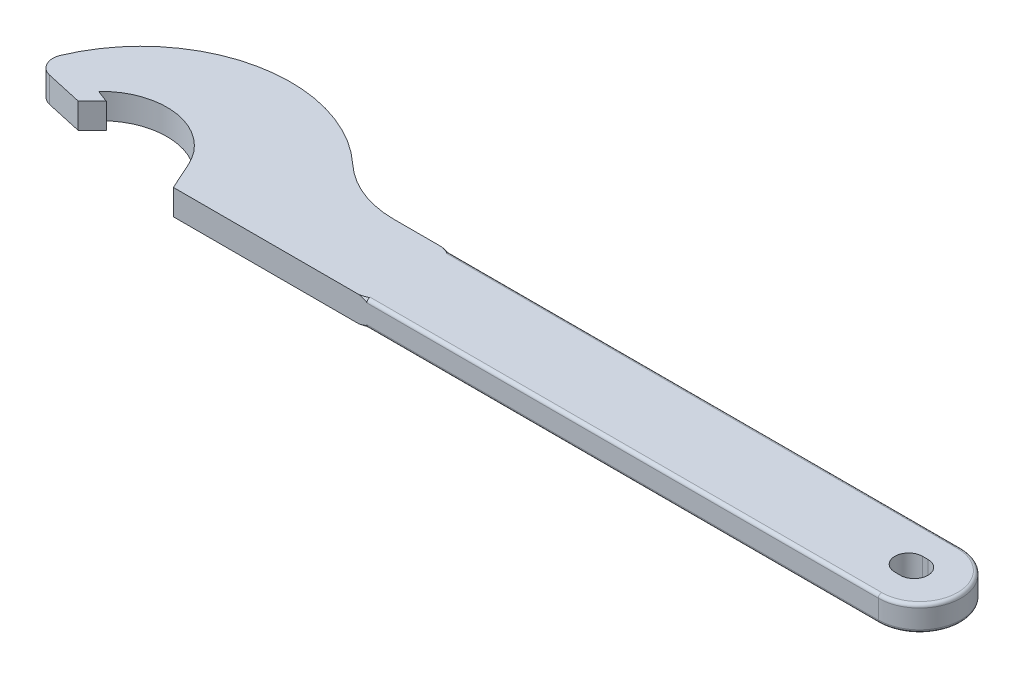
SolidWorks part; units mm, degrees
other "P01 Spanner" parameters "D1"=3.048
ref_plane "Front Plane" through (0, 0, 0) normal (0, 0, 1) x (1, 0, 0)
ref_plane "Top Plane" through (0, 0, 0) normal (0, 1, 0) x (1, 0, 0)
ref_plane "Right Plane" through (0, 0, 0) normal (1, 0, 0) x (0, 0, -1)
sketch "SK_F1_Outline" plane through (0, 0, 0) normal (0, 1, 0) x (1, 0, 0)
  line L0 (-34.3918, 0) -> (50.0534, 0)
  line L1 (50.0534, 9.9007) -> (-17.8812, 9.9007)
  line L2 (-53.4488, 4.2334) -> (-49.0587, 3.2601)
  line L3 (-49.0587, 3.2601) -> (-47.3518, 4.9205)
  line L4 (-47.3518, 4.9205) -> (-48.8359, 5.484)
  line L5 (-35.8603, 3.2601) -> (-34.3918, 0)
  arc A0 (50.0534, 0) -> (50.0534, 9.9007) centre (50.0534, 4.9503) ccw
  arc A1 (-17.8812, 9.9007) -> (-26.016, 13.113) centre (-17.8812, 21.8069) cw
  arc A2 (-26.016, 13.113) -> (-54.8496, 6.9373) centre (-38.2856, 0) ccw
  arc A3 (-54.8496, 6.9373) -> (-53.4488, 4.2334) centre (-53.0193, 6.1707) ccw
  arc A4 (-48.8359, 5.484) -> (-35.8603, 3.2601) centre (-43.0975, 0) cw
extrude "F1_Outline" add sketch "SK_F1_Outline" along normal mid plane 3.048
sketch "SK_F2_Slot" plane through (0, 0, 0) normal (0, 1, 0) x (1, 0, 0)
  line L0 (48.7354, 3.3002) -> (49.3954, 3.3002)
  line L1 (49.3954, 6.6004) -> (48.7354, 6.6004)
  arc A0 (49.3954, 3.3002) -> (49.3954, 6.6004) centre (49.3954, 4.9503) ccw
  arc A1 (48.7354, 6.6004) -> (48.7354, 3.3002) centre (48.7354, 4.9503) ccw
extrude "F2_Slot" cut sketch "SK_F2_Slot" against normal through all and the other way through all
sketch "SK_F3_StraightRounds" plane through (0, 0, 0) normal (1, 0, 0) x (0, 0, -1)
  line L0 (0, 1.1271) -> (-0.254, 1.1271)
  line L1 (-0.254, 1.1271) -> (-0.254, 1.778)
  line L2 (-0.254, 1.778) -> (0.3969, 1.778)
  line L3 (0.3969, 1.778) -> (0.3969, 1.524)
  line L4 (9.9007, 1.1271) -> (10.1547, 1.1271)
  line L5 (10.1547, 1.1271) -> (10.1547, 1.778)
  line L6 (10.1547, 1.778) -> (9.5038, 1.778)
  line L7 (9.5038, 1.778) -> (9.5038, 1.524)
  line L8 (0, -1.1271) -> (-0.254, -1.1271)
  line L9 (-0.254, -1.1271) -> (-0.254, -1.778)
  line L10 (-0.254, -1.778) -> (0.3969, -1.778)
  line L11 (0.3969, -1.778) -> (0.3969, -1.524)
  line L12 (9.9007, -1.1271) -> (10.1547, -1.1271)
  line L13 (10.1547, -1.1271) -> (10.1547, -1.778)
  line L14 (10.1547, -1.778) -> (9.5038, -1.778)
  line L15 (9.5038, -1.778) -> (9.5038, -1.524)
  arc A0 (0.3969, 1.524) -> (0, 1.1271) centre (0.3969, 1.1271) ccw
  arc A1 (9.5038, 1.524) -> (9.9007, 1.1271) centre (9.5038, 1.1271) cw
  arc A2 (0.3969, -1.524) -> (0, -1.1271) centre (0.3969, -1.1271) cw
  arc A3 (9.5038, -1.524) -> (9.9007, -1.1271) centre (9.5038, -1.1271) ccw
extrude "F3a_HandleRounds" cut sketch "SK_F3_StraightRounds" against normal blind 11.2137 and the other way blind 50.0534
ref_plane "PL_EndAxis" through (0, 0, -4.9503) normal (0, 0, 1) x (1, 0, 0)
sketch "SK_F3_EndRound" plane through (0, 0, -4.9503) normal (0, 0, 1) x (1, 0, 0)
  line L0 (50.0534, -2.54) -> (50.0534, 2.54) construction
  line L1 (55.0037, 1.1271) -> (55.2577, 1.1271)
  line L2 (55.2577, 1.1271) -> (55.2577, 1.778)
  line L3 (55.2577, 1.778) -> (54.6068, 1.778)
  line L4 (54.6068, 1.778) -> (54.6068, 1.524)
  line L5 (55.0037, -1.1271) -> (55.2577, -1.1271)
  line L6 (55.2577, -1.1271) -> (55.2577, -1.778)
  line L7 (55.2577, -1.778) -> (54.6068, -1.778)
  line L8 (54.6068, -1.778) -> (54.6068, -1.524)
  arc A0 (54.6068, 1.524) -> (55.0037, 1.1271) centre (54.6068, 1.1271) cw
  arc A1 (54.6068, -1.524) -> (55.0037, -1.1271) centre (54.6068, -1.1271) ccw
revolve "F3b_EndRound" cut sketch "SK_F3_EndRound" angle 180 mid plane about L0
ref_plane "PL_Runout_Pos" through (0, 1.1271, 0) normal (0, 1, 0) x (1, 0, 0)
ref_plane "PL_Runout_Neg" through (0, -1.1271, 0) normal (0, 1, 0) x (1, 0, 0)
sketch "SK_F4_Runout1" plane through (0, 1.1271, 0) normal (0, 1, 0) x (1, 0, 0)
  line L0 (-9.9437, 0.3969) -> (-13.416, 0.3969) construction
  line L1 (-11.2137, 0) -> (-12.146, -0.1644)
  line L2 (-12.146, -0.1644) -> (-12.146, -0.3651)
  line L3 (-12.146, -0.3651) -> (-11.2137, -0.3651)
  line L4 (-11.2137, -0.3651) -> (-11.2137, 0)
revolve "F4_Runout_Top_Pos" cut sketch "SK_F4_Runout1" angle 90 about L0
sketch "SK_F4_Runout2" plane through (0, 1.1271, 0) normal (0, 1, 0) x (1, 0, 0)
  line L0 (-9.9437, 9.5038) -> (-13.416, 9.5038) construction
  line L1 (-11.2137, 9.9007) -> (-12.146, 10.0651)
  line L2 (-12.146, 10.0651) -> (-12.146, 10.2658)
  line L3 (-12.146, 10.2658) -> (-11.2137, 10.2658)
  line L4 (-11.2137, 10.2658) -> (-11.2137, 9.9007)
revolve "F4_Runout_Bot_Pos" cut sketch "SK_F4_Runout2" angle 90 about L0
sketch "SK_F4_Runout3" plane through (0, -1.1271, 0) normal (0, 1, 0) x (1, 0, 0)
  line L0 (-9.9437, 0.3969) -> (-13.416, 0.3969) construction
  line L1 (-11.2137, 0) -> (-12.146, -0.1644)
  line L2 (-12.146, -0.1644) -> (-12.146, -0.3651)
  line L3 (-12.146, -0.3651) -> (-11.2137, -0.3651)
  line L4 (-11.2137, -0.3651) -> (-11.2137, 0)
revolve "F4_Runout_Top_Neg" cut sketch "SK_F4_Runout3" angle 90 about L0
sketch "SK_F4_Runout4" plane through (0, -1.1271, 0) normal (0, 1, 0) x (1, 0, 0)
  line L0 (-9.9437, 9.5038) -> (-13.416, 9.5038) construction
  line L1 (-11.2137, 9.9007) -> (-12.146, 10.0651)
  line L2 (-12.146, 10.0651) -> (-12.146, 10.2658)
  line L3 (-12.146, 10.2658) -> (-11.2137, 10.2658)
  line L4 (-11.2137, 10.2658) -> (-11.2137, 9.9007)
revolve "F4_Runout_Bot_Neg" cut sketch "SK_F4_Runout4" angle 90 about L0
equation "\"T\" = 0.12in"
equation "\"R_END\" = 0.194895in"
equation "\"W_HANDLE\" = 0.38979in"
equation "\"R_NECK\" = 0.46875in"
equation "\"R_HEAD\" = 0.707013in"
equation "\"R_HOOK\" = 0.078125in"
equation "\"R_JAW\" = 0.3125in"
equation "\"SLOT_R\" = 0.064965in"
equation "\"R_EDGE\" = 0.015625in"
equation "\"X_ROUND_START\" = -0.441484in"
equation "\"X_RUNOUT_END\" = -0.478189in"
equation "\"RUNOUT_ANG\" = 10.0"
equation "\"D1@F1_Outline\" = \"T\""
